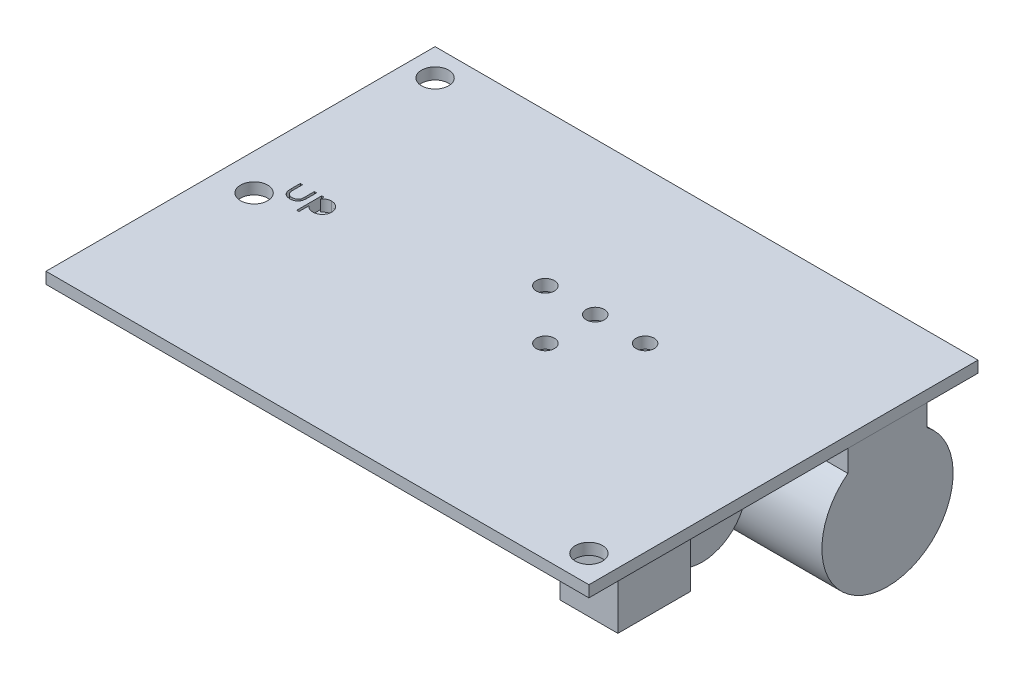
SolidWorks part; units mm, degrees
ref_plane "Front Plane" through (0, 0, 0) normal (0, 0, 1) x (1, 0, 0)
ref_plane "Top Plane" through (0, 0, 0) normal (0, 1, 0) x (1, 0, 0)
ref_plane "Right Plane" through (0, 0, 0) normal (1, 0, 0) x (0, 0, -1)
sketch "Sketch1" plane through (0, 0, 0) normal (0, 1, 0) x (1, 0, 0)
  line L1 (0, 0) -> (76.2, 0)
  line L2 (0, 0) -> (0, 54.61)
  line L3 (0, 54.61) -> (76.2, 54.61)
  line L4 (76.2, 0) -> (76.2, 54.61)
  dimension "D1" = 76.2
  dimension "D2" = 54.61
extrude "Boss-Extrude1" add sketch "Sketch1" along normal blind 1.6002
sketch "Sketch2" plane through (0, 1.6002, 0) normal (0, 1, 0) x (1, 0, 0)
  line L0 (0, 54.61) -> (0, 0) construction
  line L1 (0, 0) -> (76.2, 0) construction
  line L2 (43.815, 26.274) -> (43.815, 33.274) construction
  line L3 (43.815, 33.274) -> (50.815, 33.274) construction
  line L4 (43.815, 33.274) -> (36.815, 33.274) construction
  circle A0 centre (43.815, 33.274) radius 1.27
  circle A1 centre (36.815, 33.274) radius 1.27
  circle A2 centre (43.815, 26.274) radius 1.27
  circle A3 centre (50.815, 33.274) radius 1.27
  dimension "D1" = 43.815
  dimension "D3" = 2.54
  dimension "D4" = 7
  dimension "D2" = 33.274
extrude "Cut-Extrude1" cut sketch "Sketch2" against normal through all
sketch "Sketch3" plane through (0, 0, 0) normal (-1, 0, 0) x (0, 0, 1)
  line L0 (-47.4726, -3.048) -> (-47.4726, 0)
  line L1 (-54.61, 0) -> (0, 0) construction
  line L2 (-36.3474, -3.048) -> (-36.3474, 0)
  line L3 (-36.3474, 0) -> (-47.4726, 0)
  line L4 (-41.91, -10.3853) -> (-41.91, 6.9226) construction
  circle A0 centre (-41.91, -10.3853) radius 9.2075 construction
  arc A1 (-47.4726, -3.048) -> (-36.4063, -3.0037) centre (-41.91, -10.3853) ccw
  point P9 (-41.91, 0)
  dimension "D1" = 18.415
  dimension "D2" = 11.1252
  dimension "D3" = 3.048
  dimension "D4" = 41.91
extrude "Boss-Extrude2" add sketch "Sketch3" against normal up to vertex (76.2 mm away) separate body
sketch "Sketch5" plane through (0, 1.6002, 0) normal (0, 1, 0) x (1, 0, 0)
  line L0 (0, 54.61) -> (0, 0) construction
  line L1 (0, 0) -> (76.2, 0) construction
  circle A0 centre (5.08, 24.13) radius 1.905
  circle A1 centre (72.39, 3.81) radius 1.905
  circle A2 centre (3.81, 50.8) radius 1.905
  dimension "D1" = 5.08
  dimension "D5" = 50.8
  dimension "D7" = 3.81
  dimension "D2" = 24.13
  dimension "D3" = 72.39
  dimension "D4" = 3.81
  dimension "D6" = 3.81
extrude "Cut-Extrude4" cut sketch "Sketch5" against normal blind 12.7
sketch "Sketch4" plane through (0, 1.6002, 0) normal (0, 1, 0) x (1, 0, 0)
  text T0 "up"
extrude "Cut-Extrude2" cut sketch "Sketch4" against normal through all
sketch "Sketch6" plane through (0, 0, 0) normal (0, -1, 0) x (1, 0, 0)
  line L1 (72.644, -7.62) -> (64.516, -7.62)
  line L2 (72.644, -7.62) -> (72.644, -17.78)
  line L3 (72.644, -17.78) -> (64.516, -17.78)
  line L4 (64.516, -7.62) -> (64.516, -17.78)
  line L5 (72.644, -7.62) -> (64.516, -17.78) construction
  line L6 (64.516, -12.7) -> (72.644, -12.7) construction
  line L8 (0, -54.61) -> (0, 0) construction
  line L12 (0, 0) -> (76.2, 0) construction
  point P8 (68.58, -12.7)
  dimension "D1" = 8.128
  dimension "D2" = 10.16
  dimension "D3" = 68.58
  dimension "D4" = 12.7
extrude "Boss-Extrude3" add sketch "Sketch6" along normal blind 9.906
sketch "Sketch7" plane through (0, 0, 0) normal (0, -1, 0) x (1, 0, 0)
  line L0 (0, -54.61) -> (0, 0) construction
  line L2 (0, 0) -> (76.2, 0) construction
  circle A0 centre (57.15, -22.86) radius 8.001
  dimension "D1" = 16.002
  dimension "D2" = 57.15
  dimension "D3" = 22.86
extrude "Boss-Extrude4" [suppressed] add sketch "Sketch7" along normal blind 16.4846
ref_plane "Plane1" through (67.31, 0, 0) normal (-1, 0, 0) x (0, 0, 1)
sketch "Sketch8" plane through (67.31, 0, 0) normal (-1, 0, 0) x (0, 0, 1)
  line L1 (0, 0) -> (0, -27.0382) construction
  line L2 (0, 0) -> (-54.61, 0) construction
  circle A0 centre (-24.765, -6.2484) radius 6.2484
  dimension "D1" = 12.4968
  dimension "D2" = 24.765
extrude "Boss-Extrude5" add sketch "Sketch8" along normal blind 27.0002 separate body
